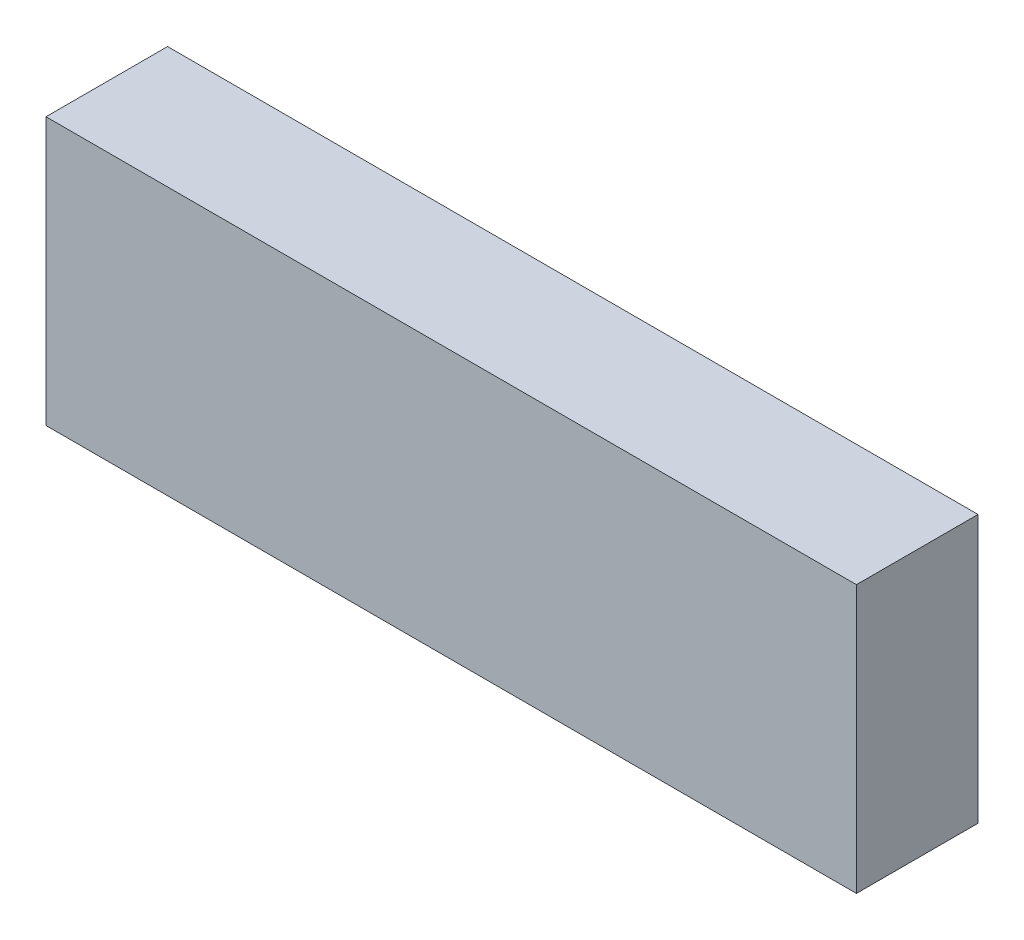
SolidWorks part; units mm, degrees
ref_plane "Plano frontal" through (0, 0, 0) normal (0, 0, 1) x (1, 0, 0)
ref_plane "Plano superior" through (0, 0, 0) normal (0, 1, 0) x (1, 0, 0)
ref_plane "Plano direito" through (0, 0, 0) normal (1, 0, 0) x (0, 0, -1)
other "Centro da massa"
sketch "Esboço1" plane through (0, 0, 0) normal (0, 0, 1) x (1, 0, 0)
  line L1 (50, -16.5) -> (-50, -16.5)
  line L2 (50, -16.5) -> (50, 16.5)
  line L3 (50, 16.5) -> (-50, 16.5)
  line L4 (-50, -16.5) -> (-50, 16.5)
  line L5 (50, -16.5) -> (-50, 16.5) construction
  line L6 (50, 16.5) -> (-50, -16.5) construction
  point P0 (0, 0)
  dimension "D1" = 100
  dimension "D2" = 33
extrude "Ressalto-extrusão1" add sketch "Esboço1" along normal blind 15
